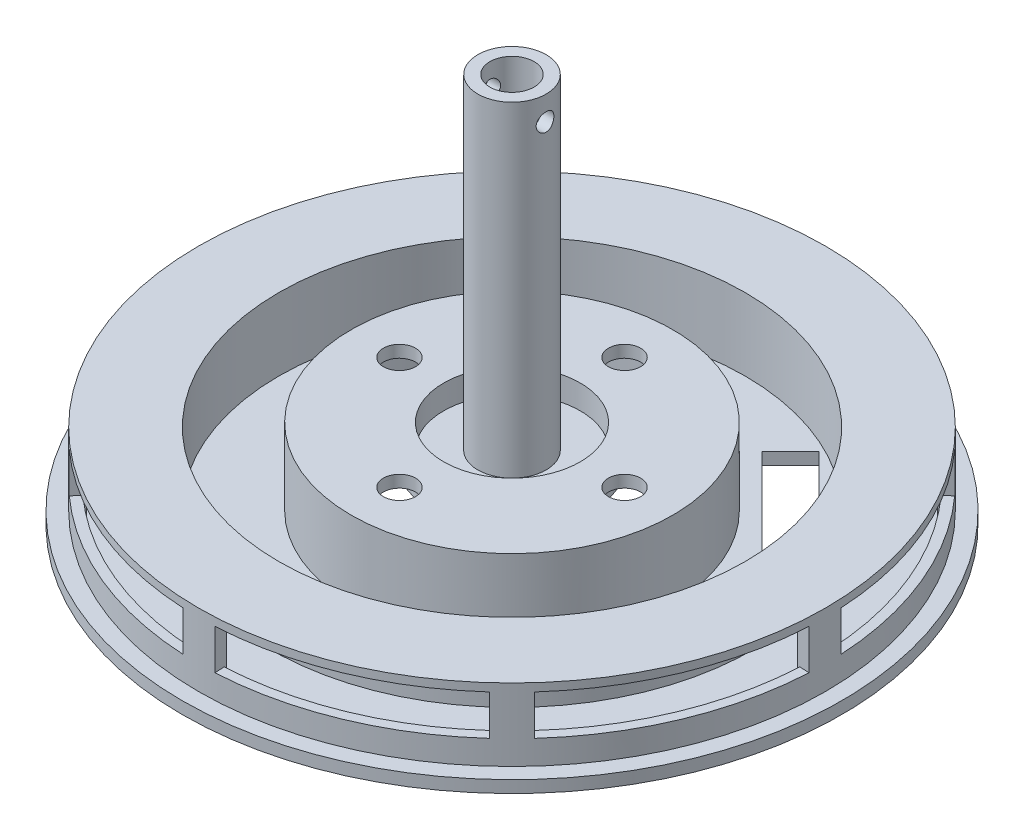
SolidWorks part; units mm, degrees
ref_plane "前视基准面" through (0, 0, 0) normal (0, 0, 1) x (1, 0, 0)
ref_plane "上视基准面" through (0, 0, 0) normal (0, 1, 0) x (1, 0, 0)
ref_plane "右视基准面" through (0, 0, 0) normal (1, 0, 0) x (0, 0, -1)
sketch "草图1" plane through (0, 0, 0) normal (0, 1, 0) x (1, 0, 0)
  circle A0 centre (0, 0) radius 10
  circle A1 centre (0, 0) radius 2.75
  dimension "D1" = 5.5
  dimension "D2" = 20
extrude "凸台-拉伸1" add sketch "草图1" along normal blind 1.5
sketch "草图2" plane through (0, 1.5, 0) normal (0, 1, 0) x (1, 0, 0)
  circle A0 centre (0, 0) radius 8.5
  circle A1 centre (0, 0) radius 10 construction
  circle A2 centre (0, 0) radius 10
  dimension "D1" = 1.5
extrude "凸台-拉伸2" add sketch "草图2" along normal blind 3
sketch "草图3" plane through (0, 1.5, 0) normal (0, 1, 0) x (1, 0, 0)
  circle A0 centre (0, 0) radius 4.25
  circle A1 centre (0, 0) radius 2.75 construction
  circle A2 centre (0, 0) radius 2.75
  dimension "D1" = 8.5
extrude "凸台-拉伸3" add sketch "草图3" along normal blind 40.5
sketch "草图4" plane through (0, 4.5, 0) normal (0, 1, 0) x (1, 0, 0)
  circle A0 centre (0, 0) radius 8.5 construction
  circle A1 centre (0, 0) radius 8.5
  circle A2 centre (0, 0) radius 20
  circle A3 centre (0, 0) radius 14 construction
  circle A4 centre (0, -14) radius 2
  circle A5 centre (-14, 0) radius 2
  circle A6 centre (14, 0) radius 2
  circle A7 centre (0, 14) radius 2
  dimension "D1" = 40
  dimension "D2" = 28
  dimension "D3" = 4
  dimension "D4" = 4
  dimension "D5" = 4
  dimension "D6" = 4
extrude "凸台-拉伸4" add sketch "草图4" against normal blind 1.5
sketch "草图5" plane through (0, 3, 0) normal (0, -1, 0) x (1, 0, 0)
  circle A0 centre (0, 0) radius 18.5
  circle A1 centre (0, 0) radius 20 construction
  circle A2 centre (0, 0) radius 20
  dimension "D1" = 1.5
extrude "凸台-拉伸5" add sketch "草图5" along normal blind 8
sketch "草图8" plane through (0, -5, 0) normal (0, -1, 0) x (1, 0, 0)
  line L0 (9.1924, -21.9203) -> (21.9203, -9.1924)
  line L1 (21.9203, -9.1924) -> (25.4558, -12.7279)
  line L2 (25.4558, -12.7279) -> (12.7279, -25.4558)
  line L3 (12.7279, -25.4558) -> (9.1924, -21.9203)
  line L4 (0, 0) -> (19.0919, -19.0919) construction
  line L5 (0, 0) -> (0, 21.0075) construction
  circle A0 centre (0, 0) radius 41
  circle A1 centre (0, 0) radius 18.5 construction
  circle A2 centre (0, 0) radius 18.5
  circle A3 centre (0, 0) radius 24 construction
  circle A4 centre (24, 0) radius 0.9
  circle A5 centre (-24, 0) radius 0.9
  circle A6 centre (0, -24) radius 0.9
  circle A7 centre (0, 24) radius 0.9
  dimension "D1" = 82
  dimension "D2" = 48
  dimension "D3" = 1.8
  dimension "D4" = 1.8
  dimension "D5" = 1.8
  dimension "D6" = 1.8
  dimension "D7" = 22
  dimension "D8" = 5
  dimension "D9" = 18
  dimension "D10" = 45
extrude "凸台-拉伸6" add sketch "草图8" along normal blind 1.5
sketch "草图9" plane through (0, -5, 0) normal (0, 1, 0) x (1, 0, 0)
  circle A0 centre (0, 0) radius 29
  circle A1 centre (0, 0) radius 30
  dimension "D1" = 1
  dimension "D2" = 58
extrude "凸台-拉伸7" add sketch "草图9" along normal blind 9
sketch "草图10" plane through (0, 4, 0) normal (0, 1, 0) x (1, 0, 0)
  circle A0 centre (0, 0) radius 39
  circle A1 centre (0, 0) radius 29 construction
  circle A2 centre (0, 0) radius 29
  dimension "D1" = 10
extrude "凸台-拉伸8" add sketch "草图10" against normal blind 1
sketch "草图12" plane through (0, -5, 0) normal (0, 1, 0) x (1, 0, 0)
  circle A0 centre (0, 0) radius 39 construction
  circle A1 centre (0, 0) radius 39
  circle A2 centre (0, 0) radius 37.8
  dimension "D1" = 1.2
extrude "凸台-拉伸9" add sketch "草图12" along normal blind 3
sketch "草图13" plane through (0, 4, 0) normal (0, 1, 0) x (1, 0, 0)
  line L0 (0, 0) -> (0, 43.2149) construction
  line L1 (0, 0) -> (1.9231, 37.4507) construction
  line L2 (1.9231, 37.4507) -> (2, 38.9487)
  line L3 (-1.9231, 37.4507) -> (-2, 38.9487)
  line L4 (25.1218, 27.8414) -> (26.1267, 28.9551)
  line L5 (27.8414, 25.1218) -> (28.9551, 26.1267)
  line L6 (37.4507, 1.9231) -> (38.9487, 2)
  line L7 (37.4507, -1.9231) -> (38.9487, -2)
  line L8 (27.8414, -25.1218) -> (28.9551, -26.1267)
  line L9 (25.1218, -27.8414) -> (26.1267, -28.9551)
  line L10 (1.9231, -37.4507) -> (2, -38.9487)
  line L11 (-1.9231, -37.4507) -> (-2, -38.9487)
  line L12 (-25.1218, -27.8414) -> (-26.1267, -28.9551)
  line L13 (-27.8414, -25.1218) -> (-28.9551, -26.1267)
  line L14 (-37.4507, -1.9231) -> (-38.9487, -2)
  line L15 (-37.4507, 1.9231) -> (-38.9487, 2)
  line L16 (-27.8414, 25.1218) -> (-28.9551, 26.1267)
  line L17 (-25.1218, 27.8414) -> (-26.1267, 28.9551)
  circle A0 centre (0, 0) radius 39 construction
  arc A1 (2, 38.9487) -> (-2, 38.9487) centre (0, 0) ccw
  arc A2 (1.9231, 37.4507) -> (-1.9231, 37.4507) centre (0, 0) ccw
  arc A3 (27.8414, 25.1218) -> (25.1218, 27.8414) centre (0, 0) ccw
  circle A4 centre (0, 0) radius 39 construction
  circle A5 centre (0, 0) radius 37.5 construction
  arc A6 (28.9551, 26.1267) -> (26.1267, 28.9551) centre (0, 0) ccw
  arc A7 (37.4507, -1.9231) -> (37.4507, 1.9231) centre (0, 0) ccw
  arc A8 (38.9487, -2) -> (38.9487, 2) centre (0, 0) ccw
  arc A9 (25.1218, -27.8414) -> (27.8414, -25.1218) centre (0, 0) ccw
  arc A10 (26.1267, -28.9551) -> (28.9551, -26.1267) centre (0, 0) ccw
  arc A11 (-1.9231, -37.4507) -> (1.9231, -37.4507) centre (0, 0) ccw
  arc A12 (-2, -38.9487) -> (2, -38.9487) centre (0, 0) ccw
  arc A13 (-27.8414, -25.1218) -> (-25.1218, -27.8414) centre (0, 0) ccw
  arc A14 (-28.9551, -26.1267) -> (-26.1267, -28.9551) centre (0, 0) ccw
  arc A15 (-37.4507, 1.9231) -> (-37.4507, -1.9231) centre (0, 0) ccw
  arc A16 (-38.9487, 2) -> (-38.9487, -2) centre (0, 0) ccw
  arc A17 (-25.1218, 27.8414) -> (-27.8414, 25.1218) centre (0, 0) ccw
  arc A18 (-26.1267, 28.9551) -> (-28.9551, 26.1267) centre (0, 0) ccw
  point P2 (37.5, 0)
  point P10 (37.2959, 11.4025)
  dimension "D2" = 4
  dimension "D1" = 1.5
  dimension "D3" = 8
extrude "凸台-拉伸10" add sketch "草图13" against normal blind 9
sketch "草图14" plane through (0, 0, 0) normal (1, 0, 0) x (0, 0, -1)
  line L0 (0, 0) -> (0, 49.5941) construction
  line L1 (2.75, 42) -> (-2.75, 42) construction
  circle A0 centre (0, 39) radius 1.1
  point P5 (0, 37.8442)
  dimension "D1" = 2.2
  dimension "D2" = 3
extrude "切除-拉伸1" cut sketch "草图14" against normal up to next and the other way up to next
